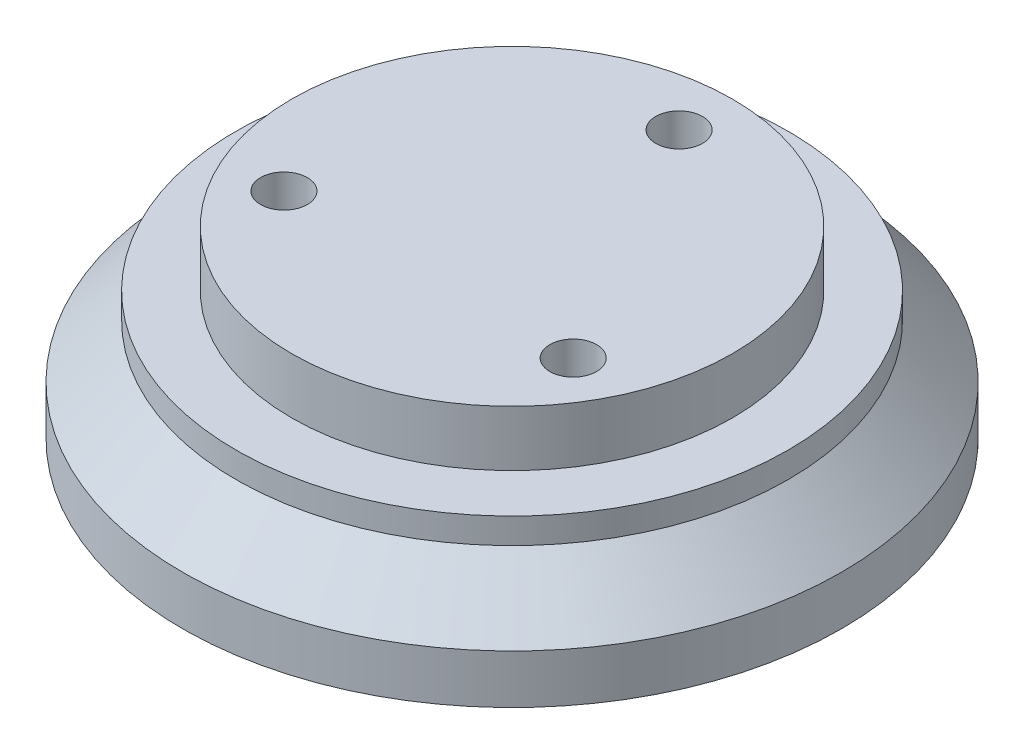
SolidWorks part; units mm, degrees
ref_plane "Front Plane" through (0, 0, 0) normal (0, 0, 1) x (1, 0, 0)
ref_plane "Top Plane" through (0, 0, 0) normal (0, 1, 0) x (1, 0, 0)
ref_plane "Right Plane" through (0, 0, 0) normal (1, 0, 0) x (0, 0, -1)
sketch "Sketch1" plane through (0, 0, 0) normal (0, 0, 1) x (1, 0, 0)
  line L0 (0, 0) -> (0, 38.625) construction
  line L1 (0, 16.5) -> (19.8, 16.5)
  line L4 (24.8, 9.2) -> (29.6, 4.4)
  line L5 (29.6, 4.4) -> (29.6, 0)
  line L6 (29.6, 0) -> (0, 0)
  line L7 (24.8, 9.2) -> (24.8, 0) construction
  line L8 (0, 0) -> (0, 16.5)
  line L10 (24.8, 9.2) -> (24.8, 11.5)
  line L11 (24.8, 11.5) -> (19.8, 11.5)
  line L12 (19.8, 11.5) -> (19.8, 16.5)
  dimension "D1" = 4.4
  dimension "D2" = 45
  dimension "D3" = 19.8
  dimension "D4" = 2.3
  dimension "D5" = 5
  dimension "D6" = 24.8
  dimension "D7" = 29.6
revolve "Revolve1" add sketch "Sketch1" angle 360 about L8
sketch "Sketch2" plane through (0, 16.5, 0) normal (0, 1, 0) x (1, 0, 0)
  line L0 (0, 0) -> (0, 15) construction
  line L1 (0, 0) -> (12.9904, -7.5) construction
  line L2 (0, 0) -> (-12.9904, -7.5) construction
  circle A0 centre (0, 0) radius 15 construction
  circle A1 centre (0, 15) radius 2.1
  circle A2 centre (-12.9904, -7.5) radius 2.1
  circle A3 centre (12.9904, -7.5) radius 2.1
  dimension "D1" = 30
  dimension "D4" = 4.2
  dimension "D2" = 120
  dimension "D3" = 120
extrude "Cut-Extrude1" cut sketch "Sketch2" against normal up to next
sketch "Sketch3" plane through (0, 0, 0) normal (0, -1, 0) x (1, 0, 0)
  line L1 (-10.8542, 11.2) -> (-15.1266, 11.2)
  line L2 (-15.1266, 11.2) -> (-17.2628, 7.5)
  line L3 (-17.2628, 7.5) -> (-15.1266, 3.8)
  line L4 (-15.1266, 3.8) -> (-10.8542, 3.8)
  line L5 (-10.8542, 3.8) -> (-8.718, 7.5)
  line L6 (-8.718, 7.5) -> (-10.8542, 11.2)
  line L7 (15.1266, 11.2) -> (10.8542, 11.2)
  line L8 (10.8542, 11.2) -> (8.718, 7.5)
  line L9 (8.718, 7.5) -> (10.8542, 3.8)
  line L10 (10.8542, 3.8) -> (15.1266, 3.8)
  line L11 (15.1266, 3.8) -> (17.2628, 7.5)
  line L12 (17.2628, 7.5) -> (15.1266, 11.2)
  line L13 (2.1362, -11.3) -> (-2.1362, -11.3)
  line L14 (-2.1362, -11.3) -> (-4.2724, -15)
  line L15 (-4.2724, -15) -> (-2.1362, -18.7)
  line L16 (-2.1362, -18.7) -> (2.1362, -18.7)
  line L17 (2.1362, -18.7) -> (4.2724, -15)
  line L18 (4.2724, -15) -> (2.1362, -11.3)
  circle A0 centre (-12.9904, 7.5) radius 3.7 construction
  circle A1 centre (12.9904, 7.5) radius 3.7 construction
  circle A2 centre (0, -15) radius 3.7 construction
  dimension "D1" = 7.4
extrude "Cut-Extrude2" cut sketch "Sketch3" against normal blind 5
